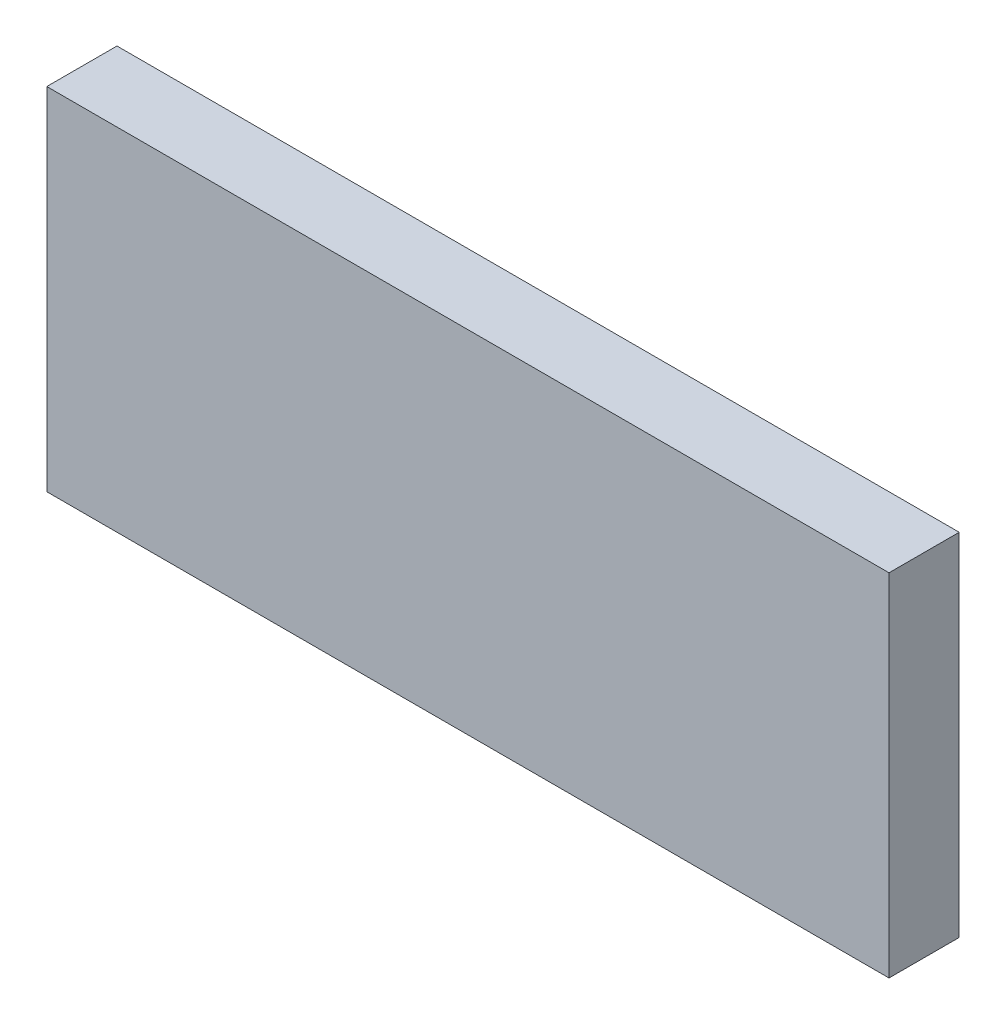
SolidWorks part; units mm, degrees
material "Pine"
ref_plane "Piano frontale" through (0, 0, 0) normal (0, 0, 1) x (1, 0, 0)
ref_plane "Piano superiore" through (0, 0, 0) normal (0, 1, 0) x (1, 0, 0)
ref_plane "Piano destro" through (0, 0, 0) normal (1, 0, 0) x (0, 0, -1)
sketch "Sketch1" plane through (0, 0, 0) normal (0, 0, 1) x (1, 0, 0)
  line L1 (0, 0) -> (18, 0)
  line L2 (0, 0) -> (0, 7.5)
  line L3 (0, 7.5) -> (18, 7.5)
  line L4 (18, 0) -> (18, 7.5)
  dimension "D1" = 18
  dimension "D2" = 7.5
extrude "Boss-Extrude1" add sketch "Sketch1" along normal blind 1.5
scale "Scale1" scale about origin uniform scaling yes scale factor 10
